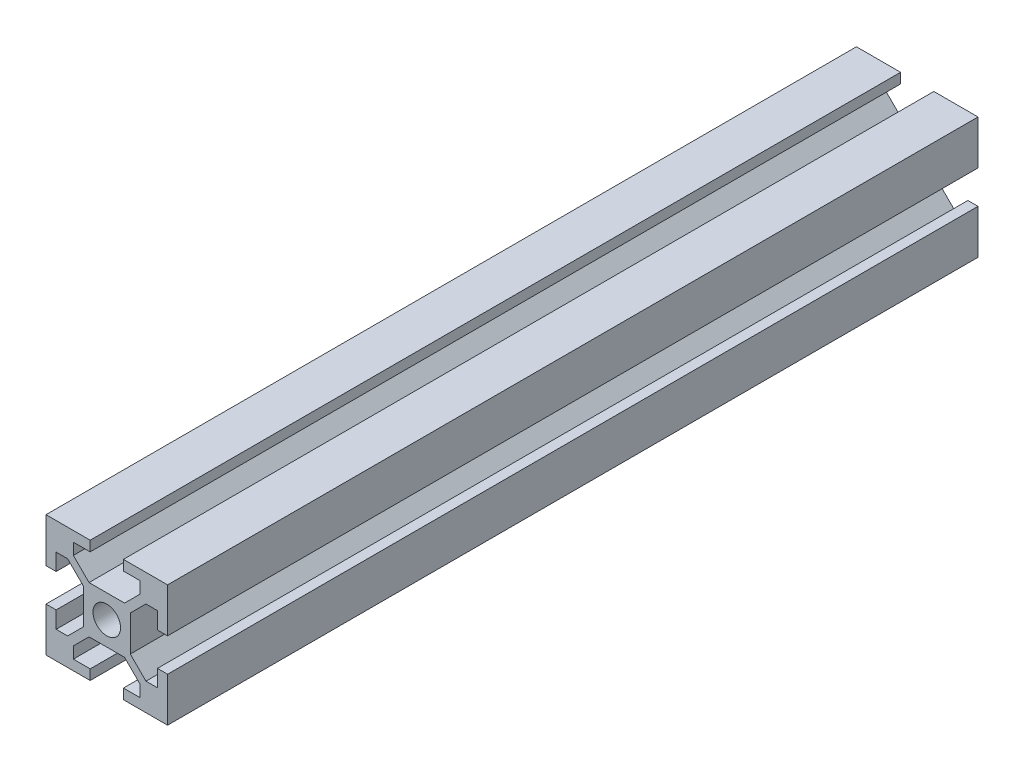
SolidWorks part; units mm, degrees
ref_plane "前视基准面" through (0, 0, 0) normal (0, 0, 1) x (1, 0, 0)
ref_plane "上视基准面" through (0, 0, 0) normal (0, 1, 0) x (1, 0, 0)
ref_plane "右视基准面" through (0, 0, 0) normal (1, 0, 0) x (0, 0, -1)
sketch "草图1" plane through (0, 0, 0) normal (0, 0, 1) x (1, 0, 0)
  line L0 (-4.1, 15) -> (-4.1, 12.5)
  line L1 (-4.3858, -5.8) -> (4.3858, -5.8)
  line L2 (-5.8, -4.3858) -> (-5.8, 4.3858)
  line L3 (-4.3858, 5.8) -> (4.3858, 5.8)
  line L4 (5.8, -4.3858) -> (5.8, 4.3858)
  line L5 (-9.6642, 8.25) -> (-12.5, 8.25)
  line L6 (-8.25, -12.5) -> (-4.1, -12.5)
  line L7 (-15, -15) -> (-4.1, -15)
  line L8 (-15, -15) -> (-15, -4.1)
  line L9 (-8.25, 15) -> (-4.1, 15)
  line L10 (15, -15) -> (15, -4.1)
  line L11 (-8.25, 9.6642) -> (-8.25, 12.5)
  line L12 (-8.25, 15) -> (-15, 15)
  line L13 (9.6642, 8.25) -> (12.5, 8.25)
  line L14 (8.25, 9.6642) -> (8.25, 12.5)
  line L15 (8.25, 15) -> (15, 15)
  line L16 (15, 8.25) -> (15, 15)
  line L17 (9.6642, -8.25) -> (12.5, -8.25)
  line L18 (8.25, -9.6642) -> (8.25, -12.5)
  line L19 (8.25, -15) -> (15, -15)
  line L20 (15, -8.25) -> (15, -15)
  line L21 (-15, 8.25) -> (-15, 15)
  line L22 (-9.6642, -8.25) -> (-12.5, -8.25)
  line L23 (-8.25, -9.6642) -> (-8.25, -12.5)
  line L24 (-8.25, -15) -> (-15, -15)
  line L25 (-15, -8.25) -> (-15, -15)
  line L26 (-12.5, -8.25) -> (-12.5, -4.1)
  line L27 (-8.25, 12.5) -> (-4.1, 12.5)
  line L28 (12.5, -8.25) -> (12.5, -4.1)
  line L29 (-8.25, 9.6642) -> (-4.3858, 5.8)
  line L30 (-9.6642, 8.25) -> (-5.8, 4.3858)
  line L31 (8.25, 9.6642) -> (4.3858, 5.8)
  line L32 (9.6642, 8.25) -> (5.8, 4.3858)
  line L33 (4.3858, -5.8) -> (8.25, -9.6642)
  line L34 (-5.8, -4.3858) -> (-9.6642, -8.25)
  line L35 (4.1, 15) -> (4.1, 12.5)
  line L36 (5.8, -4.3858) -> (9.6642, -8.25)
  line L37 (-4.3858, -5.8) -> (-8.25, -9.6642)
  line L38 (4.1, 15) -> (15, 15)
  line L39 (4.1, 12.5) -> (8.25, 12.5)
  line L40 (-4.1, -12.5) -> (-4.1, -15)
  line L41 (4.1, -15) -> (15, -15)
  line L42 (4.1, -12.5) -> (8.25, -12.5)
  line L43 (4.1, -12.5) -> (4.1, -15)
  line L44 (-15, 4.1) -> (-12.5, 4.1)
  line L45 (-15, -4.1) -> (-12.5, -4.1)
  line L46 (-15, 4.1) -> (-15, 15)
  line L47 (-12.5, 4.1) -> (-12.5, 8.25)
  line L48 (12.5, -4.1) -> (15, -4.1)
  line L49 (12.5, 4.1) -> (15, 4.1)
  line L50 (12.5, 4.1) -> (12.5, 8.25)
  line L51 (15, 4.1) -> (15, 15)
  line L52 (-15, 8.25) -> (-15, 4.1)
  line L53 (15, 8.25) -> (15, 4.1)
  line L54 (8.25, -15) -> (4.1, -15)
  line L55 (8.25, 15) -> (4.1, 15)
  circle A0 centre (0, 0) radius 3.4
extrude "凸台-拉伸1" add sketch "草图1" along normal blind 200 contours L49 L51 L16 L15 L38 L35 L39 L14 L31 L3 L29 L11 L27 L0 L9 L12 L21 L46 L44 L47 L5 L30 L2 L34 L22 L26 L45 L8 L7 L40 L6 L23 L37 L1 L33 L18 L42 L43 L41 L19 L10 L48 L28 L17 L36 L4 L32 L13
